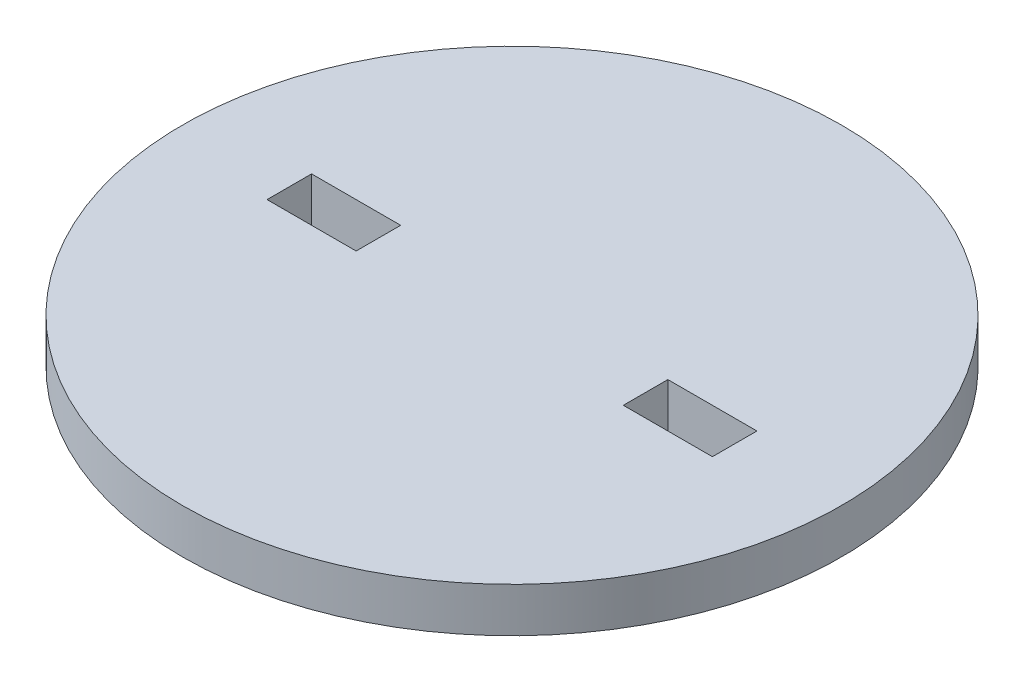
SolidWorks part; units mm, degrees
material "Cedar"
ref_plane "Front Plane" through (0, 0, 0) normal (0, 0, 1) x (1, 0, 0)
ref_plane "Top Plane" through (0, 0, 0) normal (0, 1, 0) x (1, 0, 0)
ref_plane "Right Plane" through (0, 0, 0) normal (1, 0, 0) x (0, 0, -1)
sketch "Sketch1" plane through (0, 0, 0) normal (0, 1, 0) x (1, 0, 0)
  circle A0 centre (0, 0) radius 23.495
  dimension "D1" = 46.99
extrude "Boss-Extrude1" add sketch "Sketch1" along normal blind 3.175
sketch "Sketch2" plane through (0, 3.175, 0) normal (0, 1, 0) x (1, 0, 0)
  line L0 (-9.525, 0) -> (9.525, 0) construction
  line L1 (-9.525, -1.5875) -> (-15.875, -1.5875)
  line L2 (-9.525, -1.5875) -> (-9.525, 1.5875)
  line L3 (-9.525, 1.5875) -> (-15.875, 1.5875)
  line L4 (-15.875, -1.5875) -> (-15.875, 1.5875)
  line L5 (9.525, -1.5875) -> (15.875, -1.5875)
  line L6 (9.525, -1.5875) -> (9.525, 1.5875)
  line L7 (9.525, 1.5875) -> (15.875, 1.5875)
  line L8 (15.875, -1.5875) -> (15.875, 1.5875)
  dimension "D1" = 3.175
  dimension "D2" = 6.35
  dimension "D3" = 19.05
extrude "Cut-Extrude1" cut sketch "Sketch2" against normal through all
